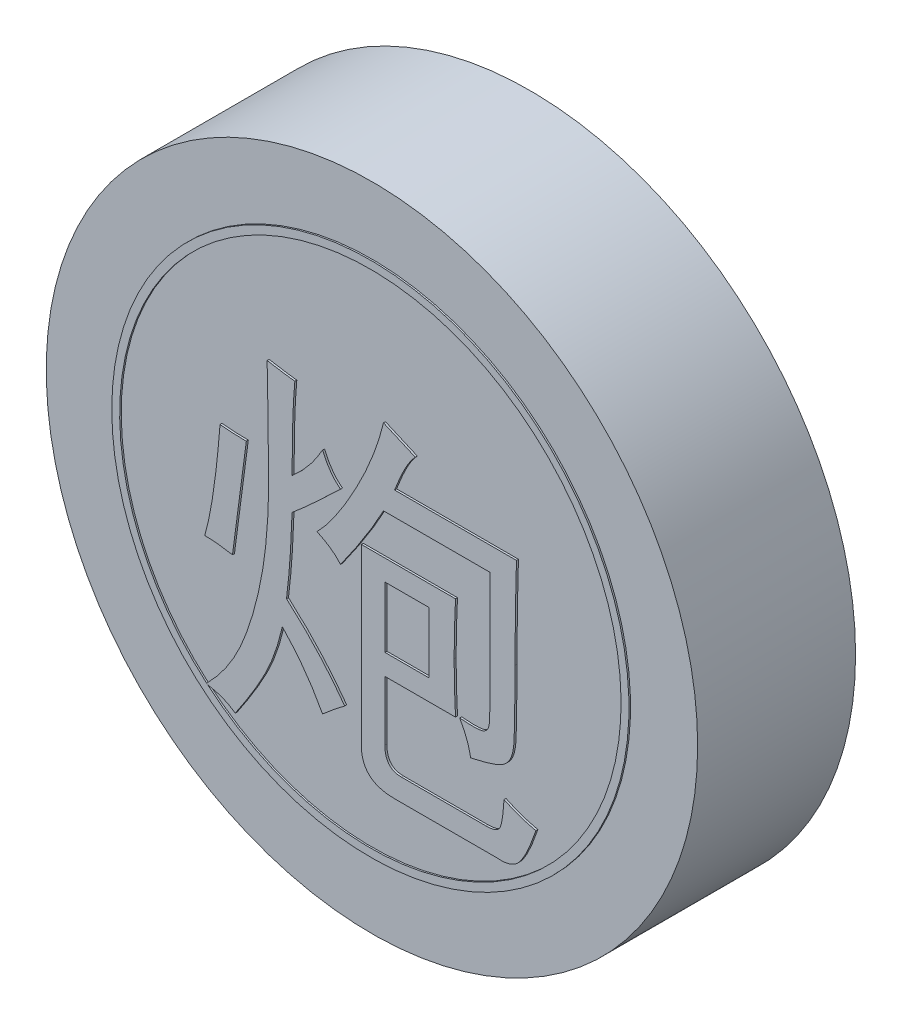
SolidWorks part; units mm, degrees
ref_plane "前视基准面" through (0, 0, 0) normal (0, 0, 1) x (1, 0, 0)
ref_plane "上视基准面" through (0, 0, 0) normal (0, 1, 0) x (1, 0, 0)
ref_plane "右视基准面" through (0, 0, 0) normal (1, 0, 0) x (0, 0, -1)
other "Configuration Table"
sketch "草图1" plane through (0, 0, 0) normal (0, 0, 1) x (1, 0, 0)
  circle A0 centre (0, 0) radius 16.5
  dimension "D1" = 33
extrude "Diameter33_Height8" add sketch "草图1" against normal blind 8
sketch "草图2" plane through (0, 0, 0) normal (0, 0, 1) x (1, 0, 0)
  text T0 "炮" font "SimHei" height 12
extrude "Character_炮" add sketch "草图2" along normal blind 0.1
sketch "草图3" plane through (0, 0, 0) normal (0, 0, 1) x (1, 0, 0)
  circle A0 centre (0, 0) radius 13.1
  circle A1 centre (0, 0) radius 12.7
extrude "Ink_ring" add sketch "草图3" along normal blind 0.08
